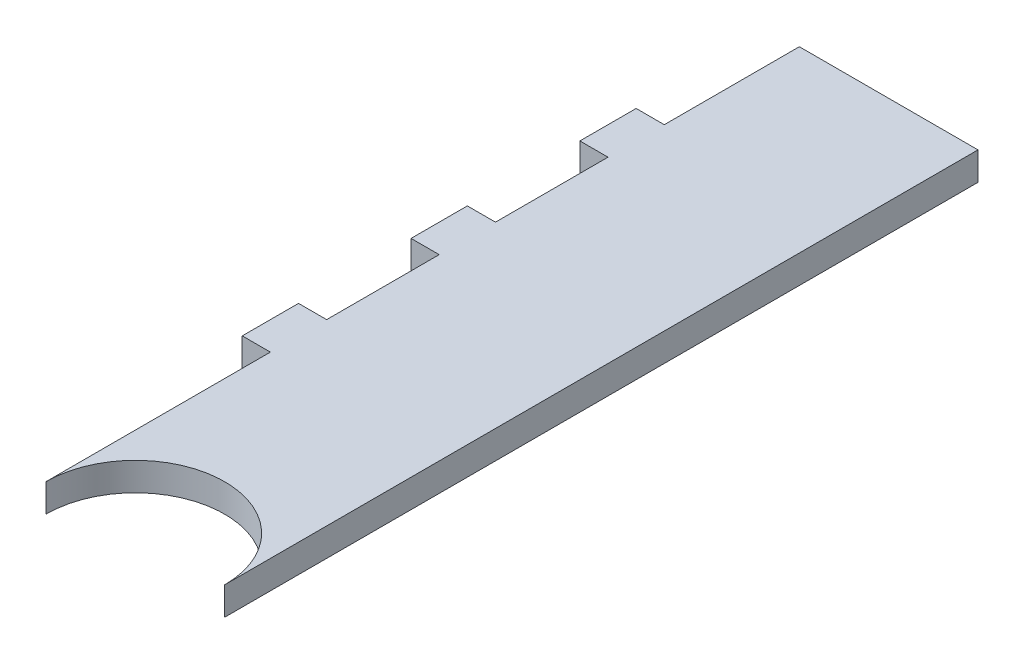
SolidWorks part; units mm, degrees
material "AISI 4130 Steel, annealed at 865C"
ref_plane "Front Plane" through (0, 0, 0) normal (0, 0, 1) x (1, 0, 0)
ref_plane "Top Plane" through (0, 0, 0) normal (0, 1, 0) x (1, 0, 0)
ref_plane "Right Plane" through (0, 0, 0) normal (1, 0, 0) x (0, 0, -1)
sketch "Sketch8" plane through (0, 0, 0) normal (0, 1, 0) x (1, 0, 0)
  line L0 (0, 15.875) -> (0, 44.875) construction
  line L1 (0, 44.875) -> (0, 74.875) construction
  line L2 (0, 74.875) -> (0, 104.875) construction
  line L3 (0, 104.875) -> (0, 133.875) construction
  line L4 (-15.875, 133.875) -> (15.875, 133.875)
  line L9 (0, 104.875) -> (-15.875, 104.875) construction
  line L10 (0, 74.875) -> (-15.875, 74.875) construction
  line L15 (0, 44.875) -> (-15.875, 44.875) construction
  line L21 (-20.875, 109.875) -> (-10.875, 109.875)
  line L22 (-20.875, 109.875) -> (-20.875, 99.875)
  line L23 (-15.875, 0) -> (-15.875, 133.875)
  line L24 (15.875, 133.875) -> (15.875, 0)
  line L25 (-20.875, 99.875) -> (-10.875, 99.875)
  line L26 (-10.875, 109.875) -> (-10.875, 99.875)
  line L27 (-20.875, 109.875) -> (-10.875, 99.875) construction
  line L28 (-20.875, 99.875) -> (-10.875, 109.875) construction
  line L29 (-20.875, 79.875) -> (-10.875, 79.875)
  line L30 (-20.875, 79.875) -> (-20.875, 69.875)
  line L31 (-20.875, 69.875) -> (-10.875, 69.875)
  line L32 (-10.875, 79.875) -> (-10.875, 69.875)
  line L33 (-20.875, 79.875) -> (-10.875, 69.875) construction
  line L34 (-20.875, 69.875) -> (-10.875, 79.875) construction
  line L35 (-20.875, 49.875) -> (-10.875, 49.875)
  line L36 (-20.875, 49.875) -> (-20.875, 39.875)
  line L37 (-20.875, 39.875) -> (-10.875, 39.875)
  line L38 (-10.875, 49.875) -> (-10.875, 39.875)
  line L39 (-20.875, 49.875) -> (-10.875, 39.875) construction
  line L40 (-20.875, 39.875) -> (-10.875, 49.875) construction
  circle A0 centre (0, 0) radius 15.875
  point P23 (0, 133.875)
  dimension "D1" = 31.75
  dimension "D2" = 29
  dimension "D3" = 30
  dimension "D4" = 10
  dimension "D6" = 31.75
sketch "Sketch9" plane through (0, 0, 0) normal (0, 1, 0) x (1, 0, 0)
  line L0 (-15.875, 109.875) -> (-15.875, 133.875)
  line L1 (-20.875, 109.875) -> (-10.875, 109.875) construction
  line L2 (-15.875, 133.875) -> (15.875, 133.875)
  line L3 (15.875, 133.875) -> (15.875, 0)
  line L4 (-15.875, 0) -> (-15.875, 39.875)
  line L5 (-20.875, 39.875) -> (-10.875, 39.875) construction
  line L6 (-15.875, 39.875) -> (-20.875, 39.875)
  line L7 (-20.875, 39.875) -> (-20.875, 49.875)
  line L8 (-20.875, 49.875) -> (-15.875, 49.875)
  line L9 (-20.875, 49.875) -> (-10.875, 49.875) construction
  line L10 (-15.875, 49.875) -> (-15.875, 69.875)
  line L11 (-20.875, 69.875) -> (-10.875, 69.875) construction
  line L12 (-15.875, 69.875) -> (-20.875, 69.875)
  line L13 (-20.875, 69.875) -> (-20.875, 79.875)
  line L14 (-20.875, 79.875) -> (-15.875, 79.875)
  line L15 (-20.875, 79.875) -> (-10.875, 79.875) construction
  line L16 (-15.875, 79.875) -> (-15.875, 99.875)
  line L17 (-20.875, 99.875) -> (-10.875, 99.875) construction
  line L18 (-15.875, 99.875) -> (-20.875, 99.875)
  line L19 (-20.875, 99.875) -> (-20.875, 109.875)
  line L20 (-20.875, 109.875) -> (-15.875, 109.875)
  circle A0 centre (0, 0) radius 15.875 construction
  arc A1 (15.875, 0) -> (-15.875, 0) centre (0, 0) ccw
extrude "Boss-Extrude1" add sketch "Sketch9" along normal blind 5
